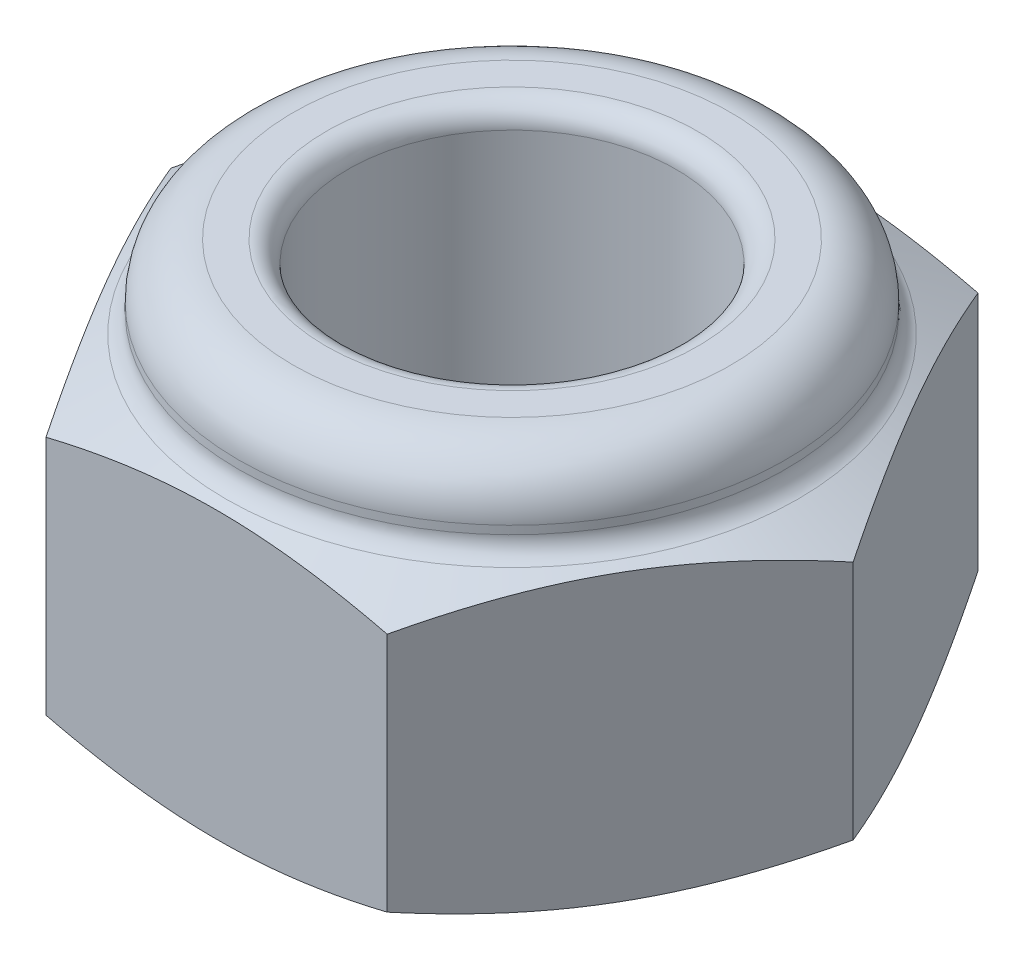
SolidWorks part; units mm, degrees
ref_plane "前视基准面" through (0, 0, 0) normal (0, 0, 1) x (1, 0, 0)
ref_plane "上视基准面" through (0, 0, 0) normal (0, 1, 0) x (1, 0, 0)
ref_plane "右视基准面" through (0, 0, 0) normal (1, 0, 0) x (0, 0, -1)
sketch "草图1" plane through (0, 0, 0) normal (0, 1, 0) x (1, 0, 0)
  line L1 (3.1177, 0) -> (1.5588, 2.7)
  line L2 (1.5588, 2.7) -> (-1.5588, 2.7)
  line L3 (-1.5588, 2.7) -> (-3.1177, 0)
  line L4 (-3.1177, 0) -> (-1.5588, -2.7)
  line L5 (-1.5588, -2.7) -> (1.5588, -2.7)
  line L6 (1.5588, -2.7) -> (3.1177, 0)
  circle A0 centre (0, 0) radius 2.7 construction
  dimension "D1" = 5.4
extrude "凸台-拉伸1" add sketch "草图1" along normal mid plane 2.8
sketch "草图2" plane through (0, 0, 0) normal (0, 0, 1) x (1, 0, 0)
  line L0 (-3.1177, 1.1) -> (-2.5, 1.4)
  line L1 (-3.1177, 1.4) -> (-3.1177, -1.4) construction
  line L2 (-3.1177, 1.4) -> (-1.5588, 1.4) construction
  line L3 (-2.5, 1.4) -> (-3.1177, 1.4)
  line L4 (-3.1177, 1.4) -> (-3.1177, 1.1)
  line L5 (0, 0) -> (0, 1.4) construction
  line L6 (-1.5588, 1.4) -> (1.5588, 1.4) construction
  dimension "D1" = 5
  dimension "D2" = 0.3
revolve "切除-旋转1" cut sketch "草图2" angle 360 about L5
mirror "镜向3" about plane through (0, 0, 0) normal (0, 1, 0) of "切除-旋转1"
sketch "草图3" plane through (0, 1.4, 0) normal (0, 1, 0) x (1, 0, 0)
  circle A0 centre (0, 0) radius 1.5
  dimension "D1" = 3
extrude "切除-拉伸1" cut sketch "草图3" against normal through all
sketch "草图4" plane through (0, 0, 0) normal (1, 0, 0) x (0, 0, -1)
  line L0 (-2.5, 1.4) -> (-2.5, 1.6)
  line L1 (-2, 2.1) -> (-1.5, 2.1)
  line L2 (-1.5, 2.1) -> (-1.5, 1.4)
  line L3 (2.5, 1.4) -> (-2.5, 1.4) construction
  line L4 (-1.5, 1.4) -> (-2.5, 1.4)
  line L5 (0, 1.4) -> (0, -1.4) construction
  line L6 (1.5, 1.4) -> (-1.5, 1.4) construction
  line L7 (-2.5, -1.4) -> (2.5, -1.4) construction
  arc A0 (-2.5, 1.6) -> (-2, 2.1) centre (-2, 1.6) cw
  dimension "D1" = 3
  dimension "D2" = 3.5
  dimension "D3" = 0.2
  dimension "D4" = 0.5
revolve "旋转1" add sketch "草图4" angle 360 about L5
fillet "圆角1" radius 0.2 2 edges at (0, 1.4, 2.5) (0, 2.1, 1.5)
